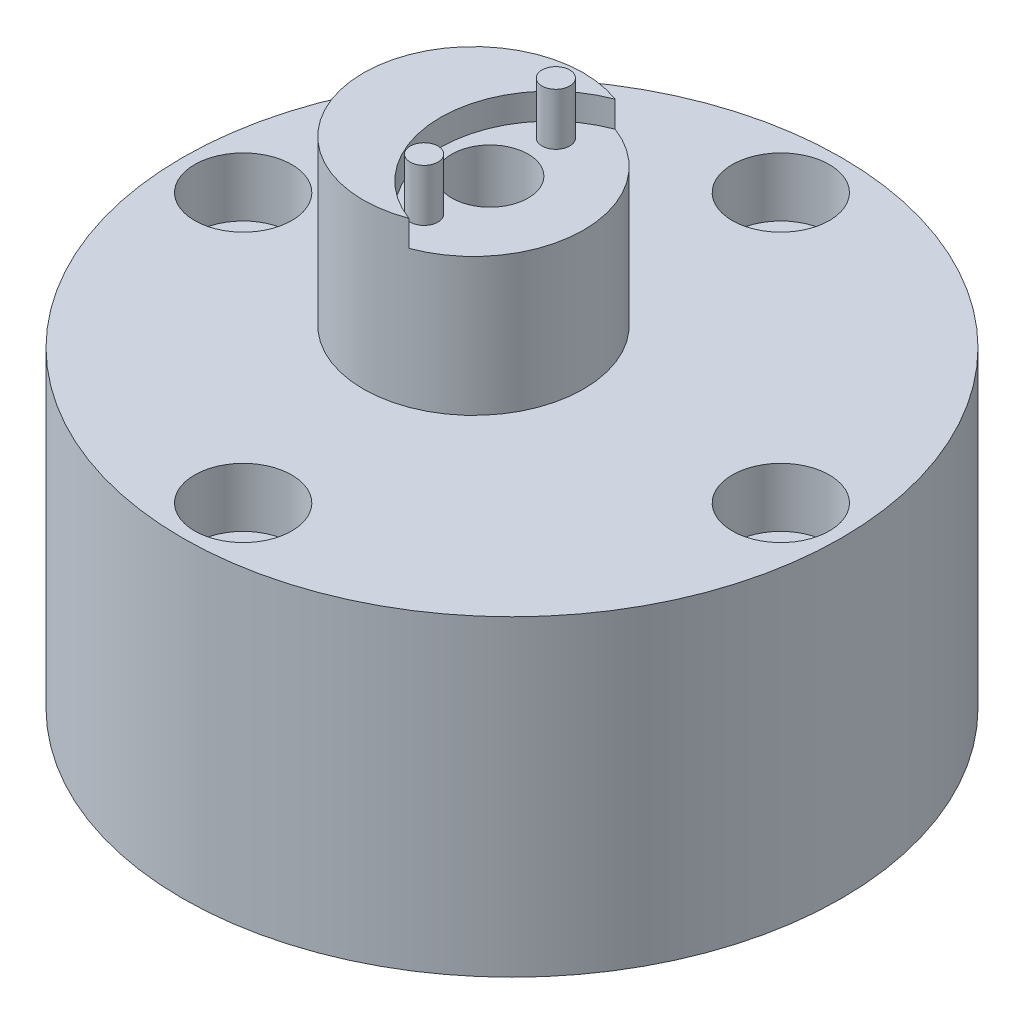
SolidWorks part; units mm, degrees
ref_plane "Front Plane" through (0, 0, 0) normal (0, 0, 1) x (1, 0, 0)
ref_plane "Top Plane" through (0, 0, 0) normal (0, 1, 0) x (1, 0, 0)
ref_plane "Right Plane" through (0, 0, 0) normal (1, 0, 0) x (0, 0, -1)
sketch "Sketch2" plane through (0, 0, 0) normal (0, 1, 0) x (1, 0, 0)
  circle A0 centre (0, 0) radius 6.35
  dimension "D1" = 12.7
extrude "Boss-Extrude1" add sketch "Sketch2" along normal blind 7.9375
sketch "Top Shaft Reference" plane through (0, 7.9375, 0) normal (0, 1, 0) x (1, 0, 0)
  line L0 (-4.1278, 0) -> (-6.35, 0) construction
  line L1 (8.5722, 0) -> (6.35, 0) construction
  line L2 (-4.1278, 0) -> (6.35, 0) construction
  circle A0 centre (2.2222, 0) radius 6.35 construction
  circle A1 centre (0, 0) radius 6.35 construction
  circle A2 centre (4.4422, 0) radius 6.35 construction
  dimension "D3" = 2.22
  dimension "D1" = 2.2222
  dimension "D2" = 2.2222
sketch "Sketch4" plane through (0, 7.9375, 0) normal (0, 1, 0) x (1, 0, 0)
  circle A2 centre (4.4422, 0) radius 6.35 construction
  circle A3 centre (0, 0) radius 6.35 construction
  arc A4 (2.2211, 5.9489) -> (2.2211, -5.9489) centre (4.4422, 0) ccw
  arc A5 (2.2211, 5.9489) -> (2.2211, -5.9489) centre (0, 0) ccw
sketch "Sketch6" plane through (0, 7.9375, 0) normal (0, 1, 0) x (1, 0, 0)
  line L0 (0.9522, 2.54) -> (0.9522, -2.54) construction
  line L1 (-4.1278, 0) -> (6.35, 0) construction
  line L2 (-4.1278, 0) -> (-1.9078, 0) construction
  circle A2 centre (0.9522, 2.54) radius 1.8 construction
  circle A3 centre (0.9522, -2.54) radius 1.8 construction
  circle A4 centre (0.9522, 0) radius 2.2
  dimension "D1" = 5.3978
  dimension "D3" = 5.08
  dimension "D2" = 3.6
  dimension "D4" = 3.6
  dimension "D5" = 4.4
  dimension "D6" = 2.86
sketch "Sketch7" plane through (0, 0, 0) normal (0, -1, 0) x (1, 0, 0)
  circle A0 centre (2.2222, 0) radius 19
  dimension "D1" = 38
extrude "Boss-Extrude5" add sketch "Sketch7" along normal blind 18 contours A0
sketch "Sketch8" plane through (0, -18, 0) normal (0, -1, 0) x (1, 0, 0)
  circle A0 centre (2.2222, 0) radius 15.5 construction
  circle A1 centre (2.2222, 15.5) radius 1.7
  circle A2 centre (17.7222, 0) radius 1.7
  circle A3 centre (2.2222, -15.5) radius 1.7
  circle A4 centre (-13.2778, 0) radius 1.7
  circle A5 centre (2.2222, 0) radius 19 construction
  dimension "D1" = 31
  dimension "D2" = 3.4
extrude "Cut-Extrude1" cut sketch "Sketch8" against normal through all
sketch "Sketch9" plane through (0, 0, 0) normal (0, 1, 0) x (1, 0, 0)
  circle A0 centre (2.2222, 15.5) radius 1.7 construction
  circle A1 centre (2.2222, 15.5) radius 1.7 construction
  circle A2 centre (2.2222, 15.5) radius 2.8
  circle A3 centre (17.7222, 0) radius 2.8
  circle A4 centre (2.2222, -15.5) radius 2.8
  circle A5 centre (-13.2778, 0) radius 2.8
  circle A6 centre (2.2222, -15.5) radius 1.7 construction
  point P13 (2.2222, 0)
  dimension "D1" = 5.6
  dimension "D2" = 4
extrude "Cut-Extrude2" cut sketch "Sketch9" against normal blind 3.4
extrude "Cut-Extrude3" cut sketch "Sketch6" against normal through all
sketch "Sketch10" plane through (0, -18, 0) normal (0, -1, 0) x (1, 0, 0)
  circle A0 centre (0.9522, 0) radius 2.2 construction
  circle A1 centre (0.9522, 0) radius 2.2 construction
  circle A2 centre (0.9522, 0) radius 3.9
  dimension "D1" = 7.8
extrude "Cut-Extrude4" cut sketch "Sketch10" against normal blind 3
extrude "Boss-Extrude6" add sketch "Sketch4" along normal blind 1.5
sketch "Sketch11" plane through (0, 7.9375, 0) normal (0, 1, 0) x (1, 0, 0)
  line L0 (0.9522, 2.2) -> (0.9522, 3.8) construction
  line L1 (0.9522, -2.2) -> (0.9522, -3.8) construction
  line L2 (0.9522, -2.2) -> (0.9522, 2.2) construction
  circle A0 centre (0.9522, 0) radius 2.2 construction
  circle A1 centre (0.9522, 0) radius 2.2 construction
  circle A2 centre (0.9522, 3.8) radius 0.8
  circle A3 centre (0.9522, -3.8) radius 0.8
  dimension "D2" = 1.6
  dimension "D1" = 1.6
extrude "Boss-Extrude7" add sketch "Sketch11" along normal blind 3
sketch "Sketch12" plane through (0, -18, 0) normal (0, -1, 0) x (1, 0, 0)
  circle A0 centre (2.2222, 0) radius 19 construction
  circle A1 centre (2.2222, 0) radius 19 construction
  circle A2 centre (2.2222, 0) radius 6
  dimension "D1" = 12
extrude "Cut-Extrude5" cut sketch "Sketch12" against normal blind 10
